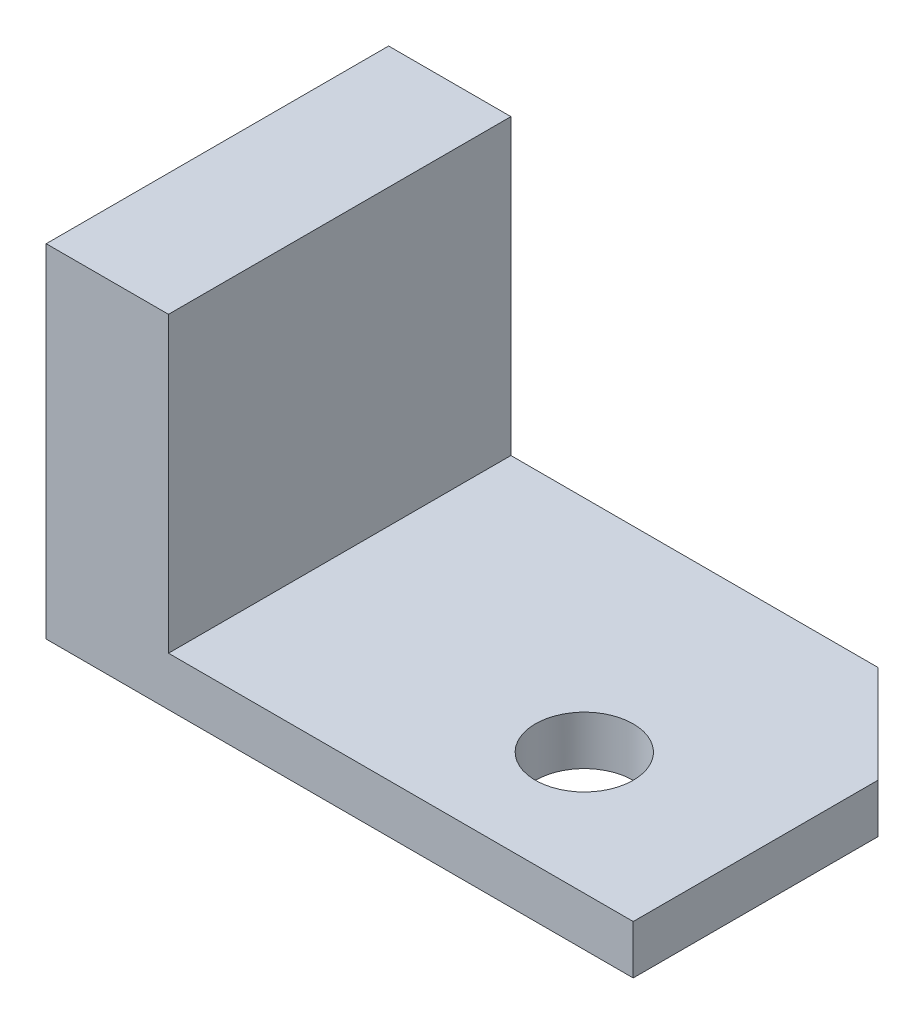
SolidWorks part; units mm, degrees
ref_plane "Front Plane" through (0, 0, 0) normal (0, 0, 1) x (1, 0, 0)
ref_plane "Top Plane" through (0, 0, 0) normal (0, 1, 0) x (1, 0, 0)
ref_plane "Right Plane" through (0, 0, 0) normal (1, 0, 0) x (0, 0, -1)
sketch "Sketch1" plane through (0, 0, 0) normal (0, 1, 0) x (1, 0, 0)
  line L1 (0, 0) -> (120, 0)
  line L2 (0, 0) -> (0, 70)
  line L3 (0, 70) -> (120, 70)
  line L4 (120, 0) -> (120, 70)
  dimension "D1" = 120
  dimension "D2" = 70
extrude "Boss-Extrude1" add sketch "Sketch1" along normal blind 10
sketch "Sketch2" plane through (0, 10, 0) normal (0, 1, 0) x (1, 0, 0)
  line L0 (120, 70) -> (0, 70) construction
  line L1 (0, 0) -> (25, 0)
  line L2 (0, 0) -> (0, 70)
  line L3 (0, 70) -> (25, 70)
  line L4 (25, 0) -> (25, 70)
  dimension "D1" = 25
extrude "Boss-Extrude2" add sketch "Sketch2" along normal blind 60
sketch "Sketch3" plane through (0, 0, 0) normal (0, 1, 0) x (1, 0, 0)
  circle A0 centre (85, 25) radius 10
  dimension "D1" = 20
  dimension "D2" = 85
  dimension "D3" = 25
extrude "Cut-Extrude1" cut sketch "Sketch3" along normal through all
chamfer "Chamfer1" distance 20 1 edges at (120, 5, -70)
